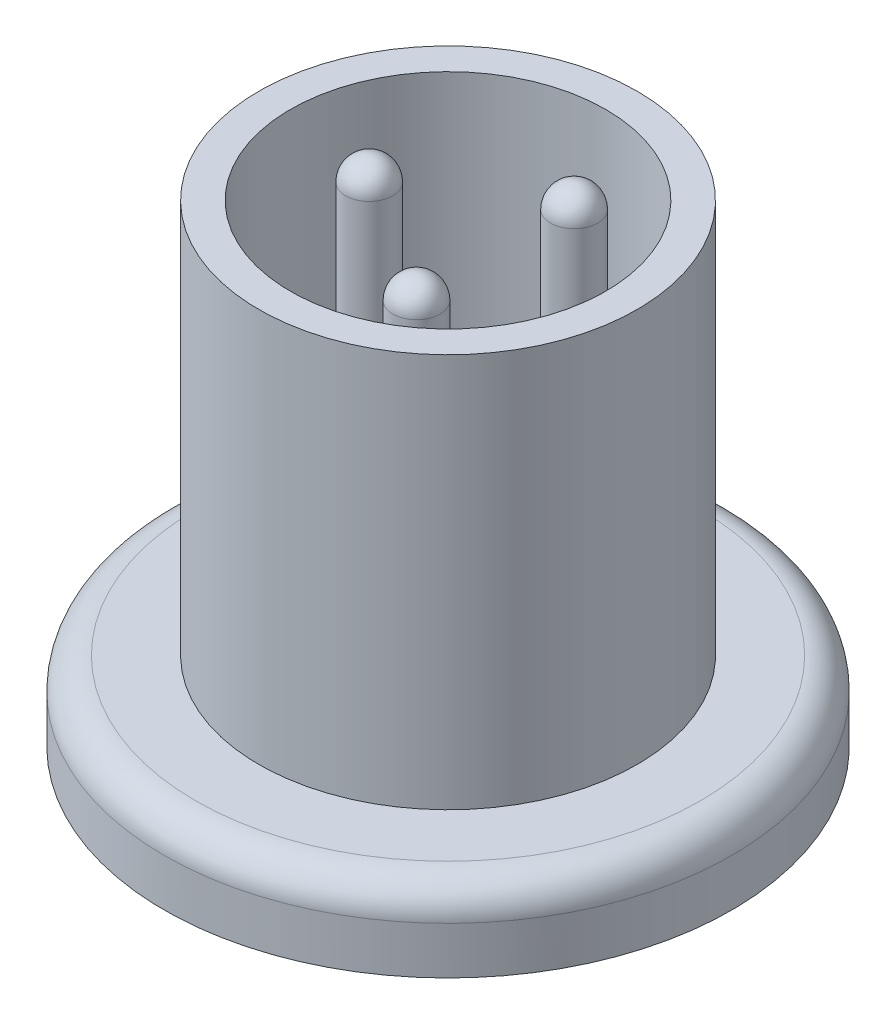
SolidWorks part; units mm, degrees
ref_plane "Front Plane" through (0, 0, 0) normal (0, 0, 1) x (1, 0, 0)
ref_plane "Top Plane" through (0, 0, 0) normal (0, 1, 0) x (1, 0, 0)
ref_plane "Right Plane" through (0, 0, 0) normal (1, 0, 0) x (0, 0, -1)
sketch "Sketch1" plane through (0, 0, 0) normal (0, 0, 1) x (1, 0, 0)
  line L0 (0, 0) -> (0, 15) construction
  line L1 (0, 0) -> (9, 0)
  line L2 (9, 0) -> (9, 2.5)
  line L3 (9, 2.5) -> (6, 2.5)
  line L4 (6, 2.5) -> (6, 15)
  line L5 (6, 15) -> (5, 15)
  line L6 (5, 15) -> (5, 3)
  line L7 (5, 3) -> (0, 3)
  line L8 (0, 3) -> (0, 0)
  dimension "D1" = 15
  dimension "D2" = 6
  dimension "D3" = 1
  dimension "D4" = 9
  dimension "D5" = 2.5
  dimension "D6" = 3
revolve "Revolve1" add sketch "Sketch1" angle 360 about L0
sketch "Sketch2" plane through (0, 3, 0) normal (0, 1, 0) x (1, 0, 0)
  line L0 (1.5, 2.5) -> (1.5, -2.5) construction
  circle A0 centre (1.5, 2.5) radius 0.75
  circle A1 centre (1.5, -2.5) radius 0.75
  circle A2 centre (-2.5, 0) radius 0.75
  point P7 (1.5, 0)
  dimension "D1" = 1.5
  dimension "D2" = 5
  dimension "D3" = 1.5
  dimension "D4" = 4
extrude "Boss-Extrude1" add sketch "Sketch2" along normal up to surface (12 mm away) up to face at (0, 15, -5)
fillet "Fillet1" radius 0.75 3 edges at (1.5, 15, 3.25) (1.5, 15, -1.75) (-2.5, 15, 0.75)
fillet "Fillet2" radius 1 1 edges at (0, 2.5, -9)
